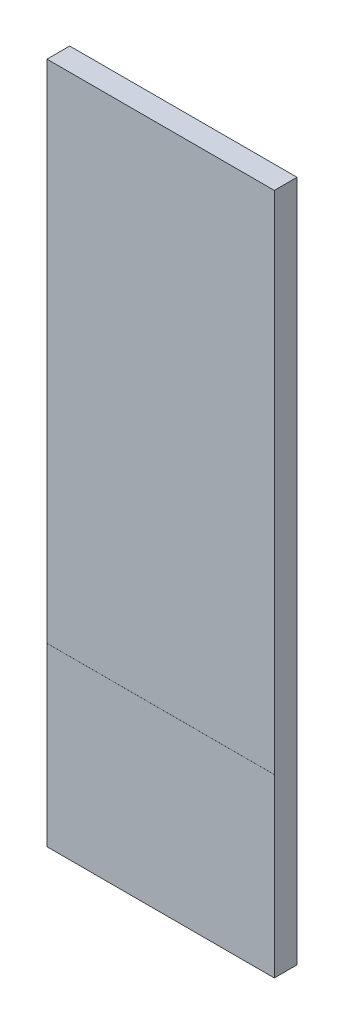
SolidWorks part; units mm, degrees
ref_plane "Front Plane" through (0, 0, 0) normal (0, 0, 1) x (1, 0, 0)
ref_plane "Top Plane" through (0, 0, 0) normal (0, 1, 0) x (1, 0, 0)
ref_plane "Right Plane" through (0, 0, 0) normal (1, 0, 0) x (0, 0, -1)
sketch "Sketch1" plane through (0, 0, 0) normal (0, 0, 1) x (1, 0, 0)
  line L1 (-20, 60) -> (20, 60)
  line L2 (-20, 60) -> (-20, -60)
  line L3 (-20, -60) -> (20, -60)
  line L4 (20, 60) -> (20, -60)
  line L5 (-20, 60) -> (20, -60) construction
  line L6 (-20, -60) -> (20, 60) construction
  point P0 (0, 0)
  dimension "D1" = 40
  dimension "D2" = 120
extrude "Boss-Extrude1" add sketch "Sketch1" along normal blind 4
sketch "Sketch4" plane through (0, 0, 4) normal (0, 0, 1) x (1, 0, 0)
  line L0 (-20, -60) -> (20, -60) construction
  line L1 (-20, -29) -> (20, -29)
  line L2 (-20, -29) -> (-20, -29.01)
  line L3 (-20, -29.01) -> (20, -29.01)
  line L4 (20, -29) -> (20, -29.01)
  line L5 (-20, 60) -> (-20, -60) construction
  line L6 (20, -60) -> (20, 60) construction
  dimension "D1" = 0.01
  dimension "D2" = 31
  dimension "D3" = 0
  dimension "D4" = 0
extrude "Cut-Extrude1" cut sketch "Sketch4" against normal blind 0.01
